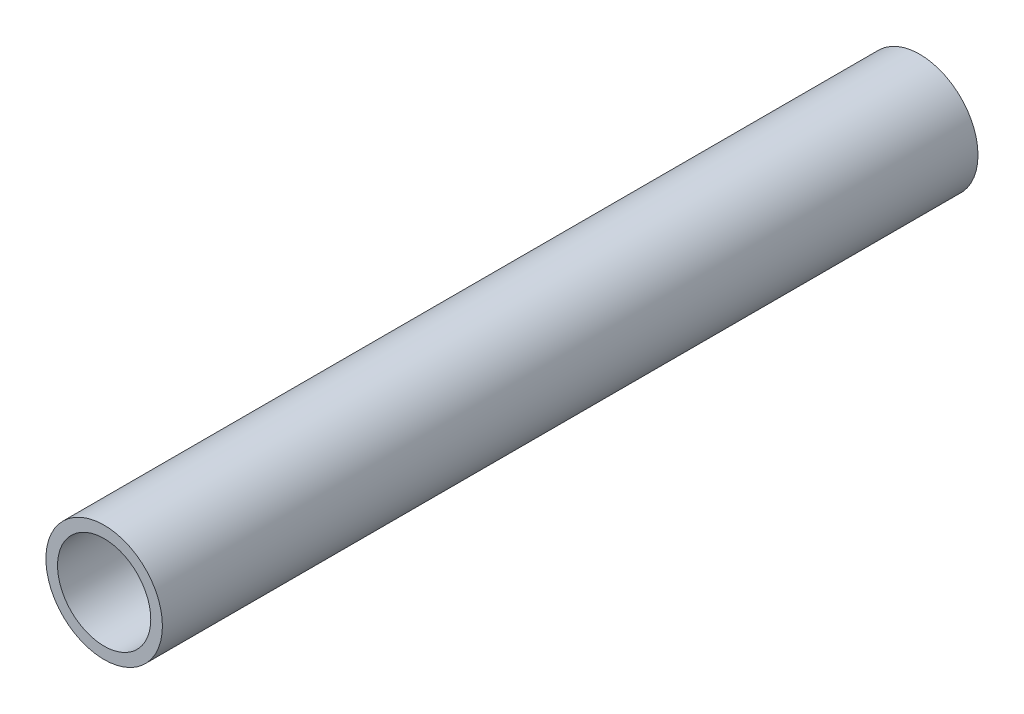
SolidWorks part; units mm, degrees
ref_plane "Front Plane" through (0, 0, 0) normal (0, 0, 1) x (1, 0, 0)
ref_plane "Top Plane" through (0, 0, 0) normal (0, 1, 0) x (1, 0, 0)
ref_plane "Right Plane" through (0, 0, 0) normal (1, 0, 0) x (0, 0, -1)
sketch "Sketch1" plane through (0, 0, 0) normal (0, 0, 1) x (1, 0, 0)
  circle A2 centre (0, 0) radius 10
  circle A3 centre (0, 0) radius 12.5
  dimension "D1" = 25
  dimension "D2" = 20
extrude "Boss-Extrude1" add sketch "Sketch1" along normal mid plane 175
